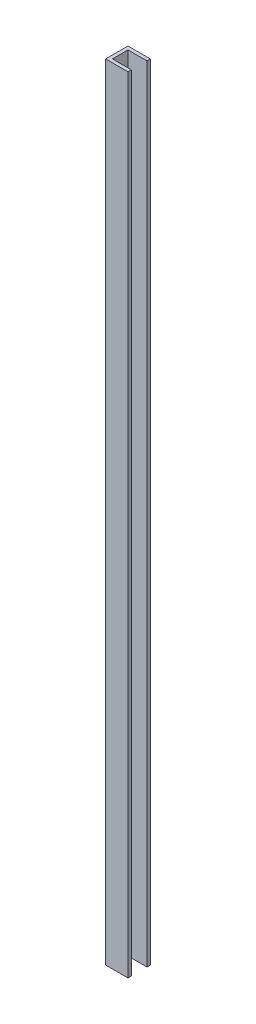
SolidWorks part; units mm, degrees
ref_plane "Front Plane" through (0, 0, 0) normal (0, 0, 1) x (1, 0, 0)
ref_plane "Top Plane" through (0, 0, 0) normal (0, 1, 0) x (1, 0, 0)
ref_plane "Right Plane" through (0, 0, 0) normal (1, 0, 0) x (0, 0, -1)
sketch "Sketch2" plane through (0, 0, 0) normal (0, 1, 0) x (1, 0, 0)
  line L1 (-5, -5) -> (5, -5)
  line L2 (-5, -5) -> (-5, 5)
  line L3 (-5, 5) -> (5, 5)
  line L4 (5, -5) -> (5, 5)
  line L5 (-5, -5) -> (5, 5) construction
  line L6 (-5, 5) -> (5, -5) construction
  line L7 (5, 3.5) -> (-3.5, 3.5)
  line L8 (5, 3.5) -> (5, -3.5)
  line L9 (5, -3.5) -> (-3.5, -3.5)
  line L10 (-3.5, 3.5) -> (-3.5, -3.5)
  point P0 (0, 0)
  dimension "D1" = 1.5
  dimension "D2" = 1.5
  dimension "D3" = 10
extrude "Boss-Extrude1" add sketch "Sketch2" along normal mid plane 352 contours L10 L7 L4 L3 L2 L1 L9
